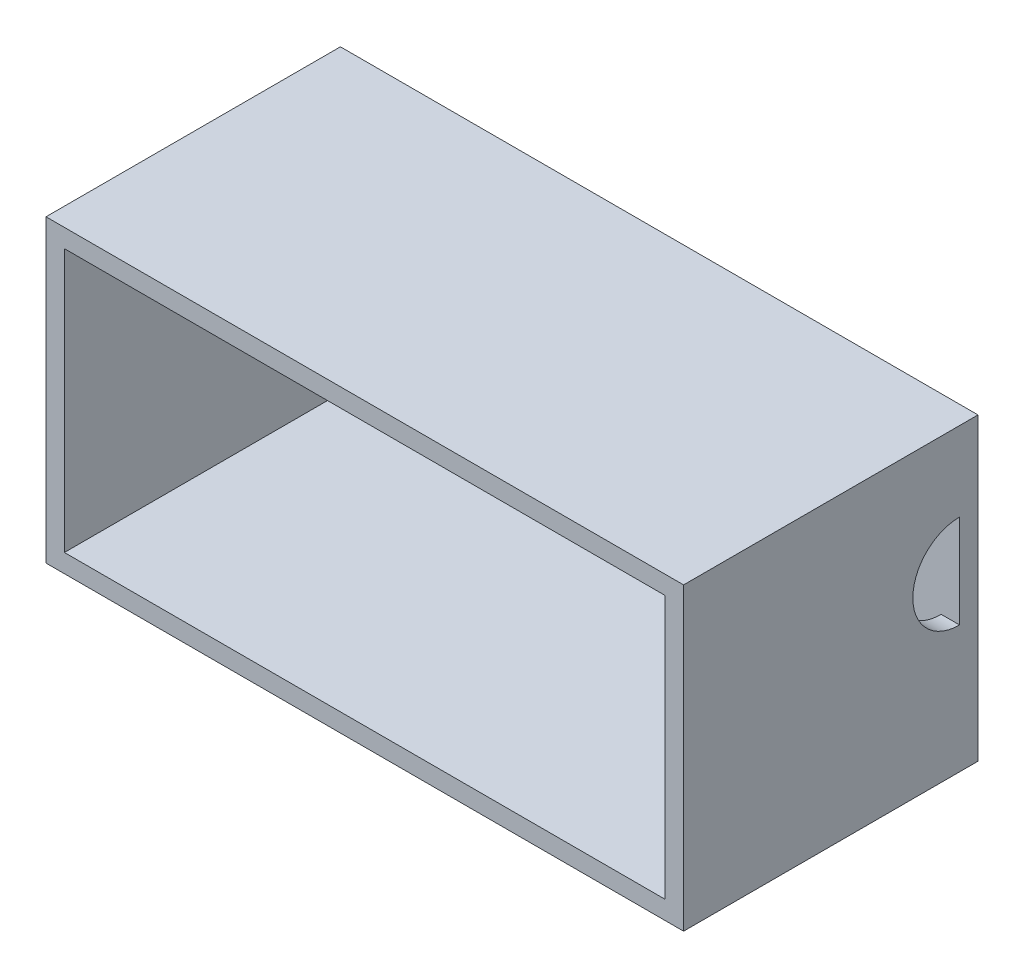
SolidWorks part; units mm, degrees
ref_plane "Plan de face" through (0, 0, 0) normal (0, 0, 1) x (1, 0, 0)
ref_plane "Plan de dessus" through (0, 0, 0) normal (0, 1, 0) x (1, 0, 0)
ref_plane "Plan de droite" through (0, 0, 0) normal (1, 0, 0) x (0, 0, -1)
sketch "Esquisse1" plane through (0, 0, 0) normal (0, 0, 1) x (1, 0, 0)
  line L1 (-24.4155, 9.7236) -> (40.8845, 9.7236)
  line L2 (-24.4155, 9.7236) -> (-24.4155, -18.8764)
  line L3 (-24.4155, -18.8764) -> (40.8845, -18.8764)
  line L4 (40.8845, 9.7236) -> (40.8845, -18.8764)
  line L5 (-26.4155, 11.7236) -> (42.8845, 11.7236)
  line L6 (-26.4155, 11.7236) -> (-26.4155, -20.8764)
  line L7 (-26.4155, -20.8764) -> (42.8845, -20.8764)
  line L8 (42.8845, 11.7236) -> (42.8845, -20.8764)
  dimension "D1" = 28.6
  dimension "D2" = 65.3
  dimension "D3" = 2
  dimension "D4" = 2
  dimension "D5" = 2
  dimension "D6" = 2
extrude "Boss.-Extru.1" add sketch "Esquisse1" along normal blind 30
ref_plane "Plan1" through (40.8845, 9.7236, 0) normal (-1, 0, 0) x (0, 0, 1)
sketch "Esquisse3" plane through (0, 0, 0) normal (0, 0, -1) x (-1, 0, 0)
  line L1 (-42.8845, 11.7236) -> (26.4155, 11.7236)
  line L2 (-42.8845, 11.7236) -> (-42.8845, -20.8764)
  line L3 (-42.8845, -20.8764) -> (26.4155, -20.8764)
  line L4 (26.4155, 11.7236) -> (26.4155, -20.8764)
extrude "Boss.-Extru.2" add sketch "Esquisse3" along normal blind 2
sketch "Esquisse4" plane through (-24.4155, 0, 0) normal (1, 0, 0) x (0, 0, -1)
  line L0 (0, 9.7236) -> (0, -18.8764) construction
  line L1 (0, -0.2764) -> (-4, -0.2764)
  line L2 (0, -0.2764) -> (0, -13.2764)
  line L3 (0, -13.2764) -> (-4, -13.2764)
  line L4 (-4, -0.2764) -> (-4, -13.2764)
  line L5 (-30, 9.7236) -> (0, 9.7236) construction
  dimension "D1" = 23
  dimension "D2" = 13
  dimension "D3" = 4
extrude "Enlèv. mat.-Extru.1" cut sketch "Esquisse4" against normal blind 18
sketch "Esquisse5" plane through (40.8845, 0, 0) normal (-1, 0, 0) x (0, 0, 1)
  line L0 (0, -18.8764) -> (0, 9.7236) construction
  line L3 (0, 3.1113) -> (0, -7.0523)
  arc A0 (0, 3.1113) -> (0, -7.0523) centre (0, -1.9705) cw
extrude "Enlèv. mat.-Extru.2" cut sketch "Esquisse5" against normal blind 18
